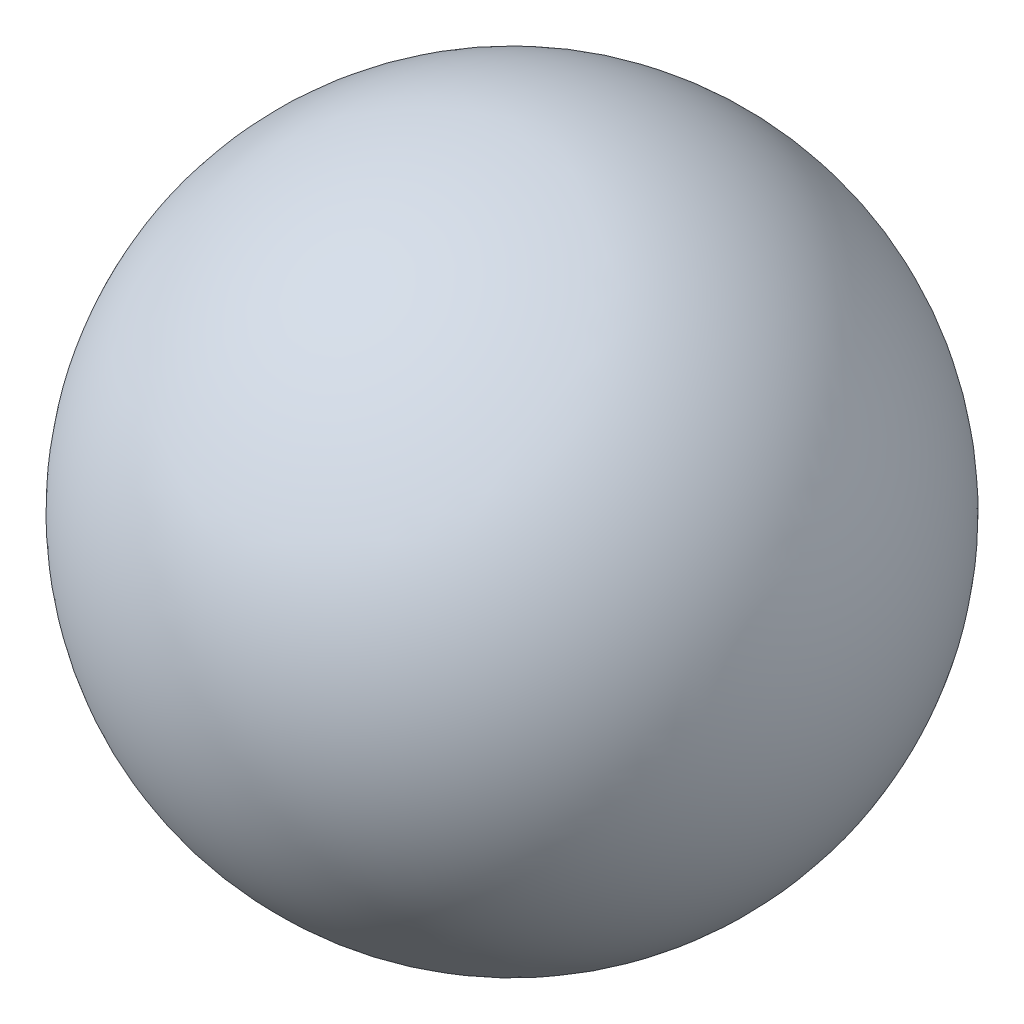
SolidWorks part; units mm, degrees
material "Plain Carbon Steel"
ref_plane "Front Plane" through (0, 0, 0) normal (0, 0, 1) x (1, 0, 0)
ref_plane "Top Plane" through (0, 0, 0) normal (0, 1, 0) x (1, 0, 0)
ref_plane "Right Plane" through (0, 0, 0) normal (1, 0, 0) x (0, 0, -1)
sketch "Sketch1" plane through (0, 0, 0) normal (0, 1, 0) x (1, 0, 0)
  line L0 (0, 0) -> (19.05, 0)
  line L1 (0, 0) -> (19.05, 0) construction
  arc A0 (19.05, 0) -> (0, 0) centre (9.525, 0) ccw
  dimension "D1" = 19.05
revolve "Revolve4" add sketch "Sketch1" angle 360 about L1
